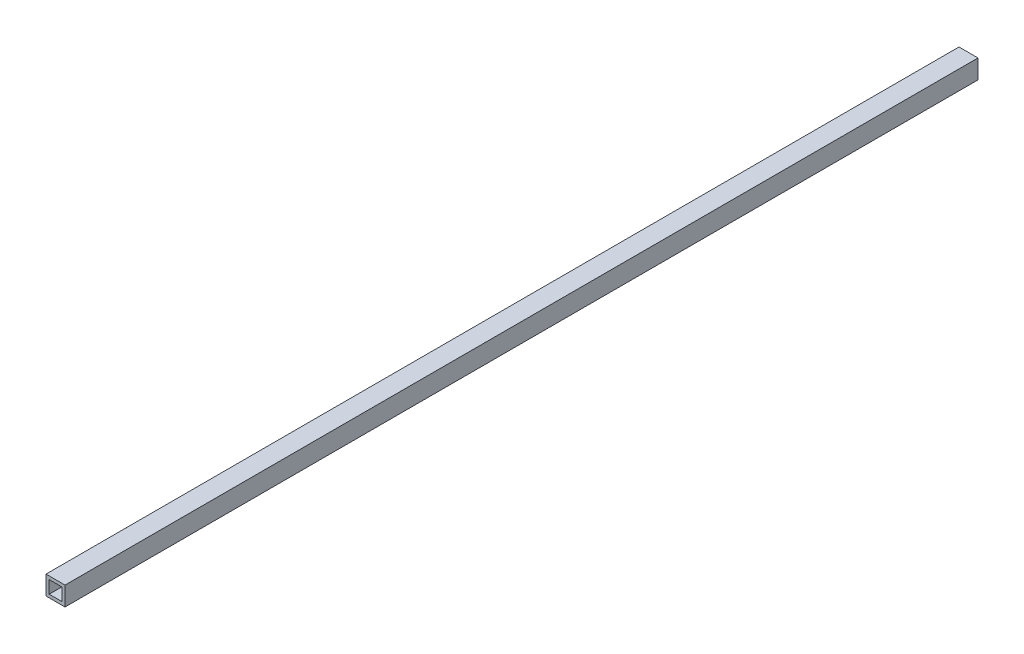
SolidWorks part; units mm, degrees
material "AISI 1020 Steel, Cold Rolled"
ref_plane "Front Plane" through (0, 0, 0) normal (0, 0, 1) x (1, 0, 0)
ref_plane "Top Plane" through (0, 0, 0) normal (0, 1, 0) x (1, 0, 0)
ref_plane "Right Plane" through (0, 0, 0) normal (1, 0, 0) x (0, 0, -1)
sketch "Sketch1" plane through (0, 0, 0) normal (0, 0, 1) x (1, 0, 0)
  line L1 (0, 0) -> (19.05, 0)
  line L2 (0, 0) -> (0, 19.05)
  line L3 (0, 19.05) -> (19.05, 19.05)
  line L4 (19.05, 0) -> (19.05, 19.05)
  dimension "D1" = 19.05
extrude "Boss-Extrude1" add sketch "Sketch1" along normal blind 914.4
sketch "Sketch3" plane through (0, 0, 914.4) normal (0, 0, 1) x (1, 0, 0)
  line L0 (0, 19.05) -> (0, 0) construction
  line L1 (3.175, 15.875) -> (15.875, 15.875)
  line L2 (3.175, 15.875) -> (3.175, 3.175)
  line L3 (3.175, 3.175) -> (15.875, 3.175)
  line L4 (15.875, 15.875) -> (15.875, 3.175)
  line L8 (3.175, 15.875) -> (0, 19.05) construction
  line L9 (3.175, 3.175) -> (0, 0) construction
  line L10 (15.875, 3.175) -> (19.05, 0) construction
  line L11 (15.875, 15.875) -> (19.05, 19.05) construction
  dimension "D1" = 3.175
extrude "Cut-Extrude1" cut sketch "Sketch3" against normal through all
